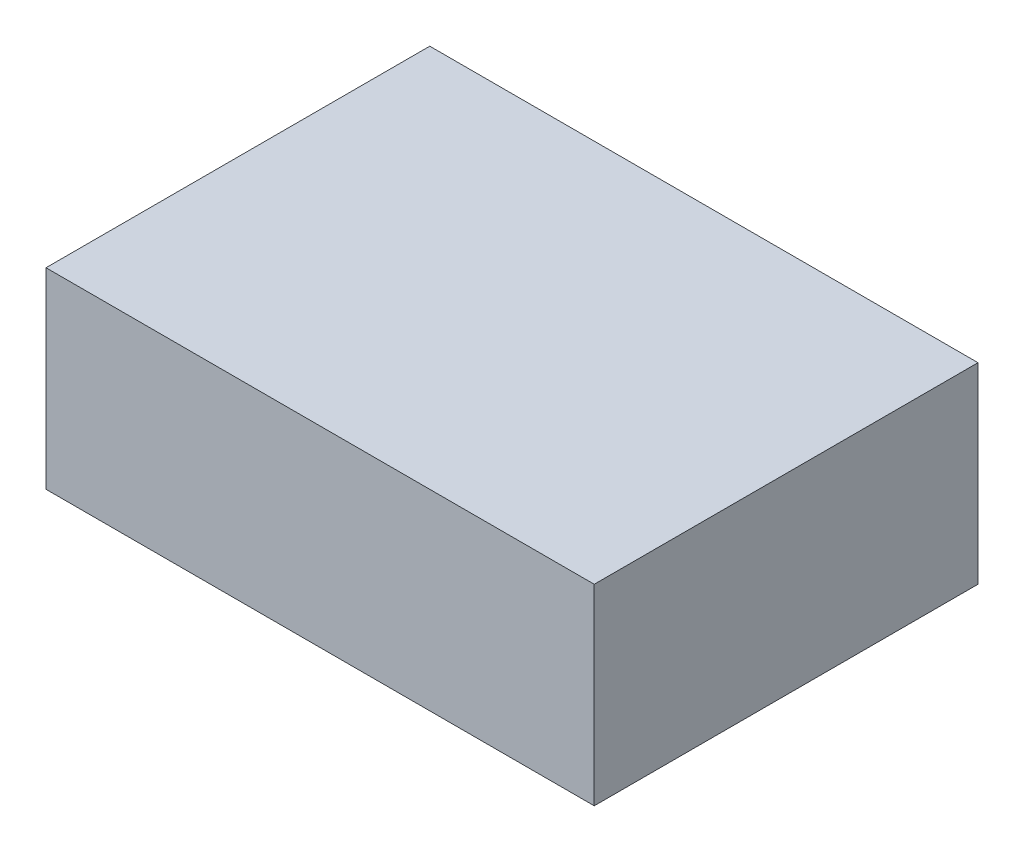
SolidWorks part; units mm, degrees
ref_plane "Ebene vorne" through (0, 0, 0) normal (0, 0, 1) x (1, 0, 0)
ref_plane "Ebene oben" through (0, 0, 0) normal (0, 1, 0) x (1, 0, 0)
ref_plane "Ebene rechts" through (0, 0, 0) normal (1, 0, 0) x (0, 0, -1)
sketch "Skizze1" plane through (0, 0, 0) normal (0, 1, 0) x (1, 0, 0)
  line L1 (-50, 35) -> (50, 35)
  line L2 (-50, 35) -> (-50, -35)
  line L3 (-50, -35) -> (50, -35)
  line L4 (50, 35) -> (50, -35)
  line L5 (-50, 35) -> (50, -35) construction
  line L6 (-50, -35) -> (50, 35) construction
  point P0 (0, 0)
  dimension "D1" = 100
  dimension "D2" = 70
extrude "Aufsatz-Linear austragen1" add sketch "Skizze1" along normal blind 35
